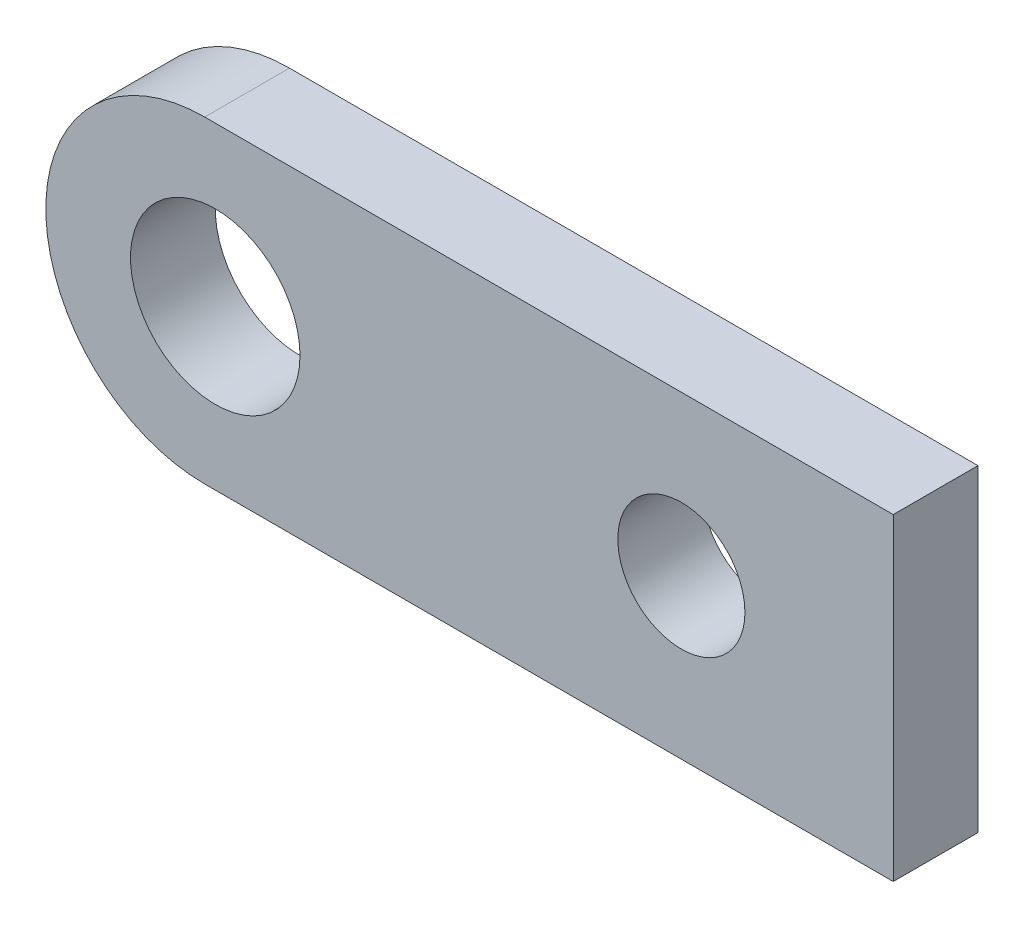
SolidWorks part; units mm, degrees
ref_plane "Спереди" through (0, 0, 0) normal (0, 0, 1) x (1, 0, 0)
ref_plane "Сверху" through (0, 0, 0) normal (0, 1, 0) x (1, 0, 0)
ref_plane "Справа" through (0, 0, 0) normal (1, 0, 0) x (0, 0, -1)
sketch "Эскиз1" plane through (0, 0, 0) normal (0, 0, 1) x (1, 0, 0)
  line L0 (0, 7.5) -> (40, 7.5) construction
  line L1 (7.5032, 0) -> (40, 0)
  line L3 (7.5032, 15) -> (40, 15)
  line L4 (40, 0) -> (40, 15)
  circle A0 centre (8, 7.5) radius 4
  circle A1 centre (30, 7.5) radius 3
  arc A2 (7.5032, 15) -> (7.5032, 0) centre (7.5032, 7.5) ccw
  dimension "D3" = 8
  dimension "D5" = 6
  dimension "D1" = 15
extrude "Бобышка-Вытянуть1" add sketch "Эскиз1" along normal blind 4
